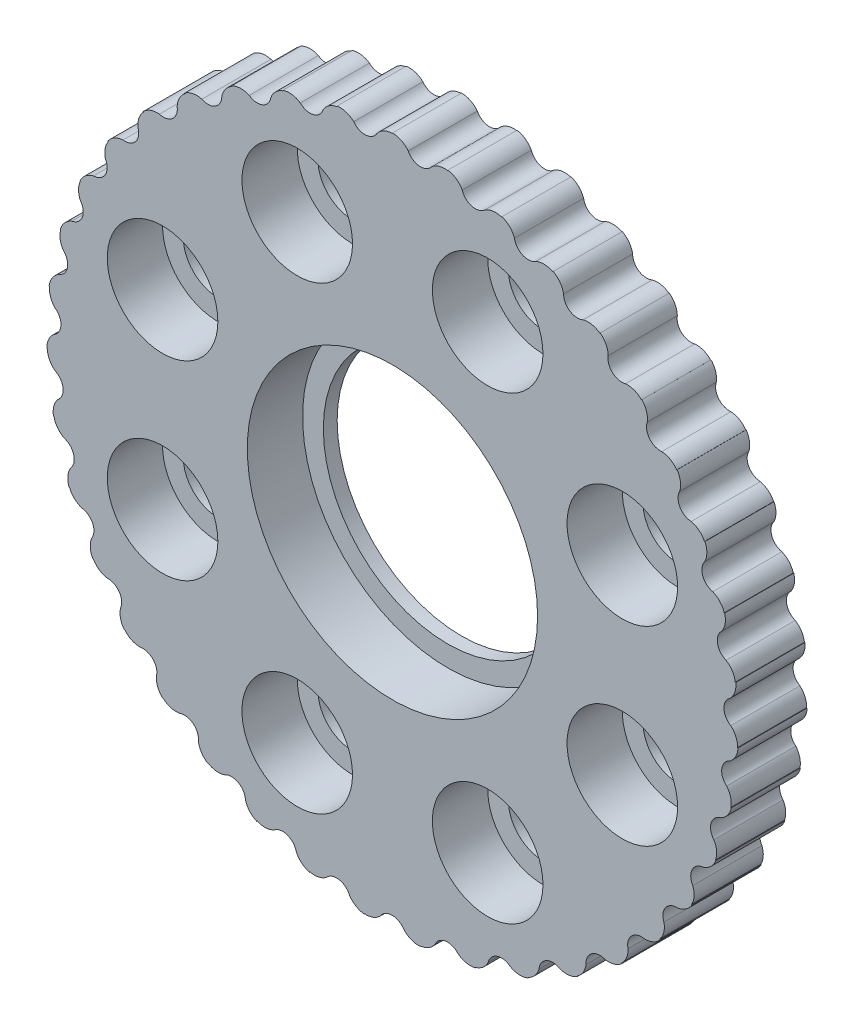
SolidWorks part; units mm, degrees
ref_plane "Plan de face" through (0, 0, 0) normal (0, 0, 1) x (1, 0, 0)
ref_plane "Plan de dessus" through (0, 0, 0) normal (0, 1, 0) x (1, 0, 0)
ref_plane "Plan de droite" through (0, 0, 0) normal (1, 0, 0) x (0, 0, -1)
sketch "Esquisse1" plane through (0, 0, 0) normal (0, 0, 1) x (1, 0, 0)
  line L0 (0, 18) -> (0, 27.9712) construction
  line L1 (0, 25.02) -> (0, 0)
  line L2 (0, 0) -> (5.0142, 23.9582)
  arc A7 (0, 25.02) -> (1.1384, 24.468) centre (0, 23.57) cw
  arc A8 (1.1384, 24.468) -> (2.824, 24.3069) centre (2.0318, 24.9173) ccw
  arc A9 (2.824, 24.3069) -> (5.0142, 23.9582) centre (3.7809, 23.2648) cw
  point P128 (0, 0)
  dimension "D2" = 23.57
  dimension "D7" = 1
  dimension "D10" = 1.45
  dimension "D3" = 25
  dimension "D8" = 3.7809
extrude "Boss.-Extru.1" add sketch "Esquisse1" along normal blind 5
pattern_circular "Répétition circulaire1" count 39 every 9.231 about axis through (0, 0, 0) along (0, 0, 1) of "Boss.-Extru.1"
sketch "Esquisse2" plane through (0, 0, 5) normal (0, 0, 1) x (1, 0, 0)
  line L0 (0, 0) -> (6.8883, 16.6298) construction
  line L1 (0, 0) -> (0, 33.0867) construction
  circle A0 centre (6.8883, 16.6298) radius 4
  circle A1 centre (0, 0) radius 10.5
  circle A9 centre (16.6298, 6.8883) radius 4
  circle A10 centre (16.6298, -6.8883) radius 4
  circle A11 centre (6.8883, -16.6298) radius 4
  circle A12 centre (-6.8883, -16.6298) radius 4
  circle A13 centre (-16.6298, -6.8883) radius 4
  circle A14 centre (-16.6298, 6.8883) radius 4
  circle A15 centre (-6.8883, 16.6298) radius 4
  point P21 (0, 0)
  point P23 (0, 0)
  dimension "D2" = 8
  dimension "D3" = 21
  dimension "D1" = 18
  dimension "D4" = 22.5
  dimension "D5" = 8
extrude "Enlèv. mat.-Extru.1" cut sketch "Esquisse2" against normal blind 4
sketch "Esquisse4" plane through (0, 0, 1) normal (0, 0, 1) x (1, 0, 0)
  circle A0 centre (0, 0) radius 9
  circle A1 centre (6.8883, 16.6298) radius 2.5
  circle A2 centre (16.6298, 6.8883) radius 2.5
  circle A3 centre (16.6298, -6.8883) radius 2.5
  circle A4 centre (6.8883, -16.6298) radius 2.5
  circle A5 centre (-6.8883, -16.6298) radius 2.5
  circle A6 centre (-16.6298, -6.8883) radius 2.5
  circle A7 centre (-16.6298, 6.8883) radius 2.5
  circle A8 centre (-6.8883, 16.6298) radius 2.5
  point P22 (0, 0)
  dimension "D1" = 18
  dimension "D2" = 5
  dimension "D3" = 8
extrude "Enlèv. mat.-Extru.2" cut sketch "Esquisse4" against normal through all
